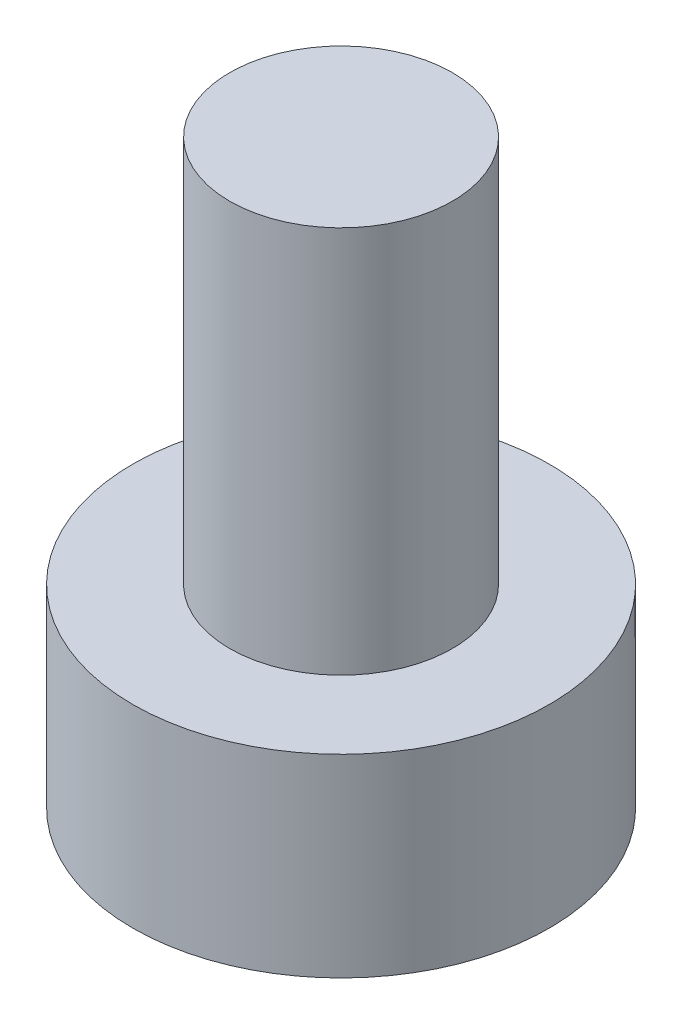
SolidWorks part; units mm, degrees
ref_plane "Front Plane" through (0, 0, 0) normal (0, 0, 1) x (1, 0, 0)
ref_plane "Top Plane" through (0, 0, 0) normal (0, 1, 0) x (1, 0, 0)
ref_plane "Right Plane" through (0, 0, 0) normal (1, 0, 0) x (0, 0, -1)
sketch "Sketch1" plane through (0, 0, 0) normal (0, 1, 0) x (1, 0, 0)
  circle A0 centre (0, 0) radius 2.15
  dimension "D1" = 4.3
extrude "Boss-Extrude1" add sketch "Sketch1" along normal blind 2
sketch "Sketch2" plane through (0, 2, 0) normal (0, 1, 0) x (1, 0, 0)
  circle A0 centre (0, 0) radius 1.15
  dimension "D1" = 2.3
extrude "Boss-Extrude2" add sketch "Sketch2" along normal blind 4
